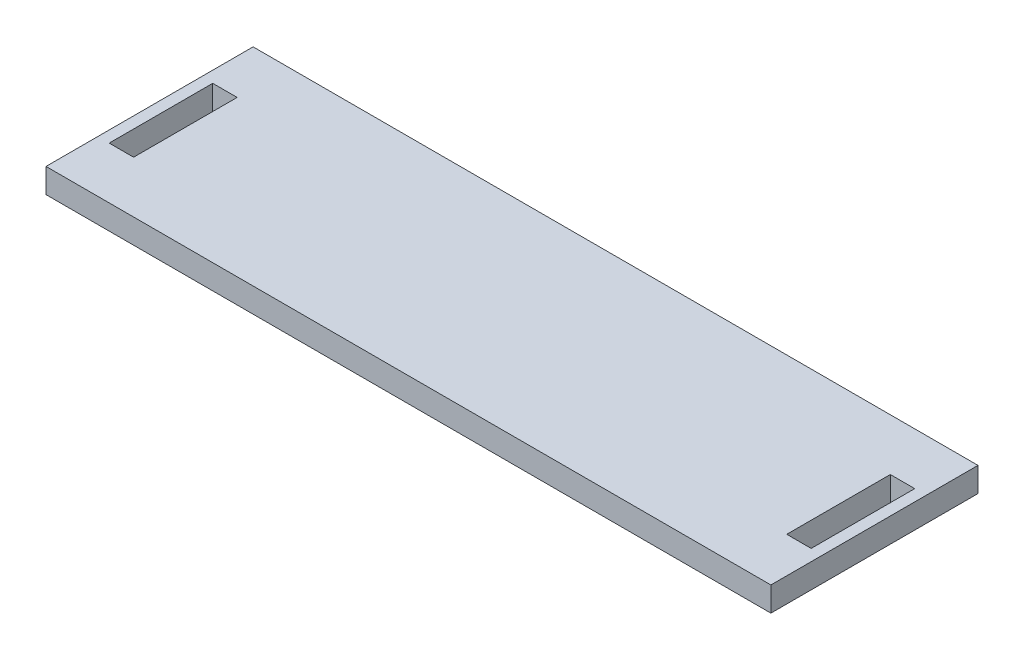
SolidWorks part; units mm, degrees
ref_plane "Front Plane" through (0, 0, 0) normal (0, 0, 1) x (1, 0, 0)
ref_plane "Top Plane" through (0, 0, 0) normal (0, 1, 0) x (1, 0, 0)
ref_plane "Right Plane" through (0, 0, 0) normal (1, 0, 0) x (0, 0, -1)
sketch "Sketch1" plane through (0, 0, 0) normal (0, 1, 0) x (1, 0, 0)
  line L1 (0, 0) -> (177.8, 0)
  line L2 (0, 0) -> (0, -50.8)
  line L3 (0, -50.8) -> (177.8, -50.8)
  line L4 (177.8, 0) -> (177.8, -50.8)
  line L5 (2.794, -12.7) -> (8.7884, -12.7)
  line L6 (2.794, -12.7) -> (2.794, -38.1)
  line L7 (2.794, -38.1) -> (8.7884, -38.1)
  line L8 (8.7884, -12.7) -> (8.7884, -38.1)
  line L9 (174.9828, -12.7) -> (168.9884, -12.7)
  line L10 (174.9828, -12.7) -> (174.9828, -38.1)
  line L11 (174.9828, -38.1) -> (168.9884, -38.1)
  line L12 (168.9884, -12.7) -> (168.9884, -38.1)
  point P9 (2.794, -25.4)
  point P10 (0, -25.4)
  point P15 (174.9828, -25.4)
  point P16 (177.8, -25.4)
  dimension "D1" = 177.8
  dimension "D2" = 50.8
  dimension "D3" = 25.4
  dimension "D4" = 5.9944
  dimension "D5" = 160.2
  dimension "D6" = 5.9944
  dimension "D7" = 25.4
  dimension "D8" = 2.794
extrude "Boss-Extrude1" add sketch "Sketch1" along normal blind 5.9944
